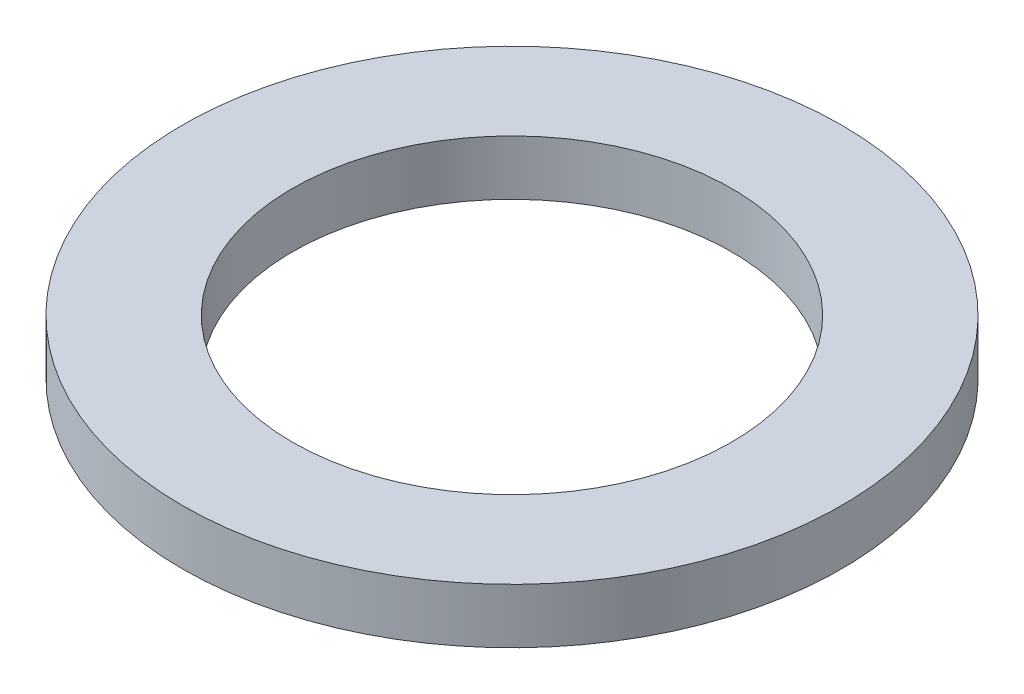
SolidWorks part; units mm, degrees
material "ｽﾃﾝﾚｽ鋼(ｸﾛﾑ)"
ref_plane "正面" through (0, 0, 0) normal (0, 0, 1) x (1, 0, 0)
ref_plane "平面" through (0, 0, 0) normal (0, 1, 0) x (1, 0, 0)
ref_plane "右側面" through (0, 0, 0) normal (1, 0, 0) x (0, 0, -1)
sketch "ｽｹｯﾁ1" plane through (0, 0, 0) normal (0, 1, 0) x (1, 0, 0)
  circle A0 centre (0, 0) radius 3
  circle A1 centre (0, 0) radius 2
  dimension "D1" = 6
  dimension "D2" = 4
extrude "ﾎﾞｽ - 押し出し1" add sketch "ｽｹｯﾁ1" along normal blind 0.5
